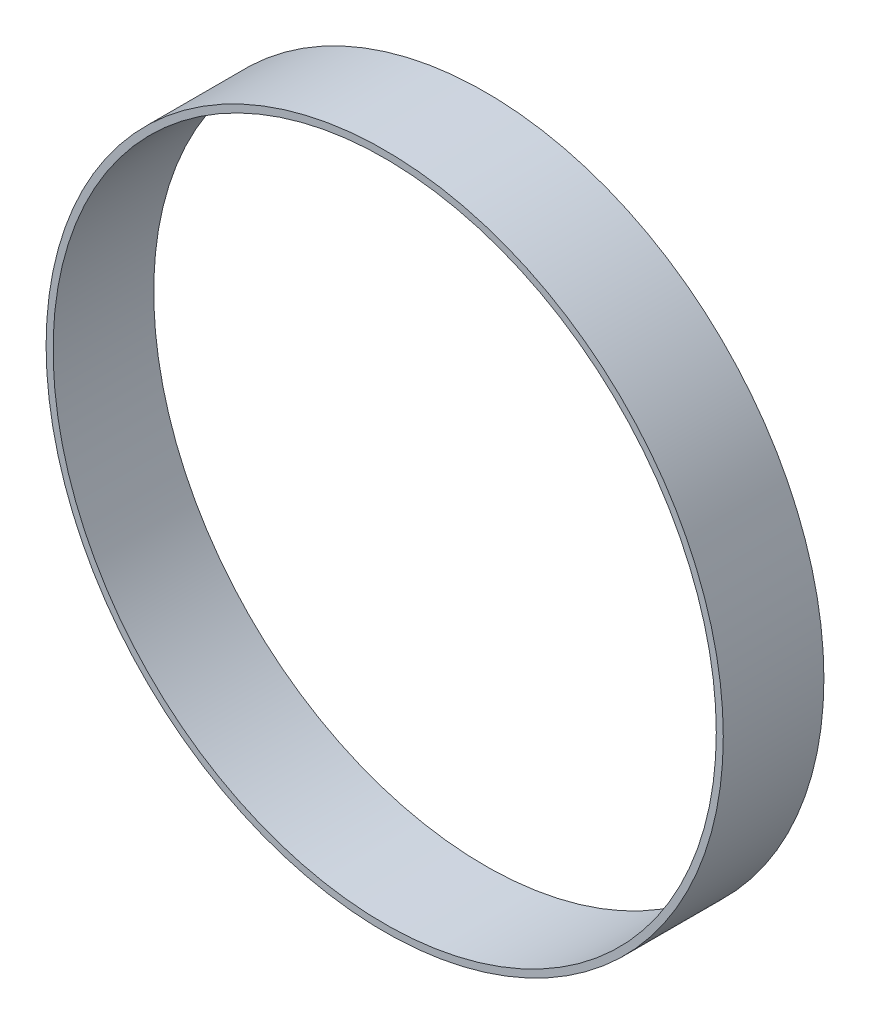
SolidWorks part; units mm, degrees
ref_plane "Plan de face" through (0, 0, 0) normal (0, 0, 1) x (1, 0, 0)
ref_plane "Plan de dessus" through (0, 0, 0) normal (0, 1, 0) x (1, 0, 0)
ref_plane "Plan de droite" through (0, 0, 0) normal (1, 0, 0) x (0, 0, -1)
sketch "Esquisse1" plane through (0, 0, 0) normal (0, 0, 1) x (1, 0, 0)
  circle A0 centre (0, 0) radius 37.9
  circle A1 centre (0, 0) radius 38.7
  dimension "D1" = 75.8
  dimension "D2" = 77.4
extrude "Boss.-Extru.1" add sketch "Esquisse1" along normal blind 11.5
